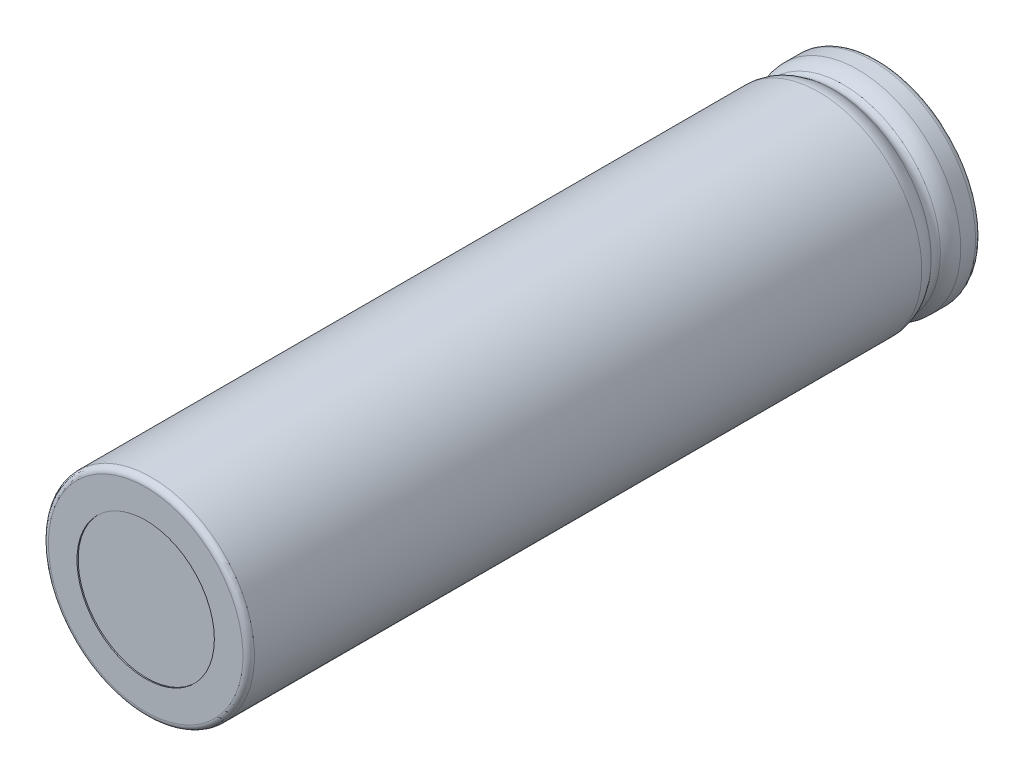
SolidWorks part; units mm, degrees
material "1060 Alloy"
ref_plane "Front Plane" through (0, 0, 0) normal (0, 0, 1) x (1, 0, 0)
ref_plane "Top Plane" through (0, 0, 0) normal (0, 1, 0) x (1, 0, 0)
ref_plane "Right Plane" through (0, 0, 0) normal (1, 0, 0) x (0, 0, -1)
sketch "Sketch2" plane through (0, 0, 0) normal (1, 0, 0) x (0, 0, -1)
  line L0 (-1000, 0) -> (49000, 0) construction
  line L1 (0, 0) -> (0, 9)
  line L2 (0, 9) -> (59.875, 9)
  line L3 (64, 9) -> (64, 3.075)
  line L4 (64, 3.075) -> (65, 3.075)
  line L5 (65, 3.075) -> (65, 0)
  line L6 (65, 0) -> (0, 0)
  line L7 (61.125, 9) -> (64, 9)
  arc A0 (59.875, 9) -> (61.125, 9) centre (60.5, 9) ccw
  point P10 (60.5, 8.375)
  dimension "D1" = 6.15
  dimension "D2" = 18
  dimension "D3" = 3.5
  dimension "D4" = 1
  dimension "D5" = 16.75
  dimension "D6" = 65
revolve "Revolve1" add sketch "Sketch2" angle 360 about L0
fillet "Fillet1" radius 0.5 2 edges at (9, 0, 0) (9, 0, -64)
fillet "Fillet2" radius 2 2 edges at (9, 0, -61.125) (9, 0, -59.875)
fillet "Fillet3" radius 0.2 1 edges at (3.075, 0, -65)
sketch "Sketch3" plane through (0, 0, 0) normal (0, 0, 1) x (1, 0, 0)
  circle A0 centre (0, 0) radius 6
  dimension "D1" = 12
extrude "Cut-Extrude1" cut sketch "Sketch3" against normal blind 0.1
sketch "Sketch4" plane through (0, 0, -64) normal (0, 0, -1) x (-1, 0, 0)
  circle A0 centre (0, 0) radius 3.1
  circle A1 centre (0, 0) radius 7.5
  dimension "D1" = 6.2
  dimension "D2" = 15
extrude "Cut-Extrude2" cut sketch "Sketch4" against normal blind 0.1
ref_plane "Plane1" through (-9, 0, 0) normal (-1, 0, 0) x (0, 0, 1)
sketch "Sketch5" [suppressed] plane through (-9, 0, 0) normal (-1, 0, 0) x (0, 0, 1)
  line L0 (-56, -2) -> (-6, -2) construction
  line L1 (-1000, 0) -> (49000, 0) construction
  line L2 (-64, 8.5) -> (-64, -8.5) construction
  line L3 (0, -8.5) -> (0, 8.5) construction
  text T0 "18650 3.7v 3300mAh"
  dimension "D1" = 8
  dimension "D2" = 6
  dimension "D3" = 2
